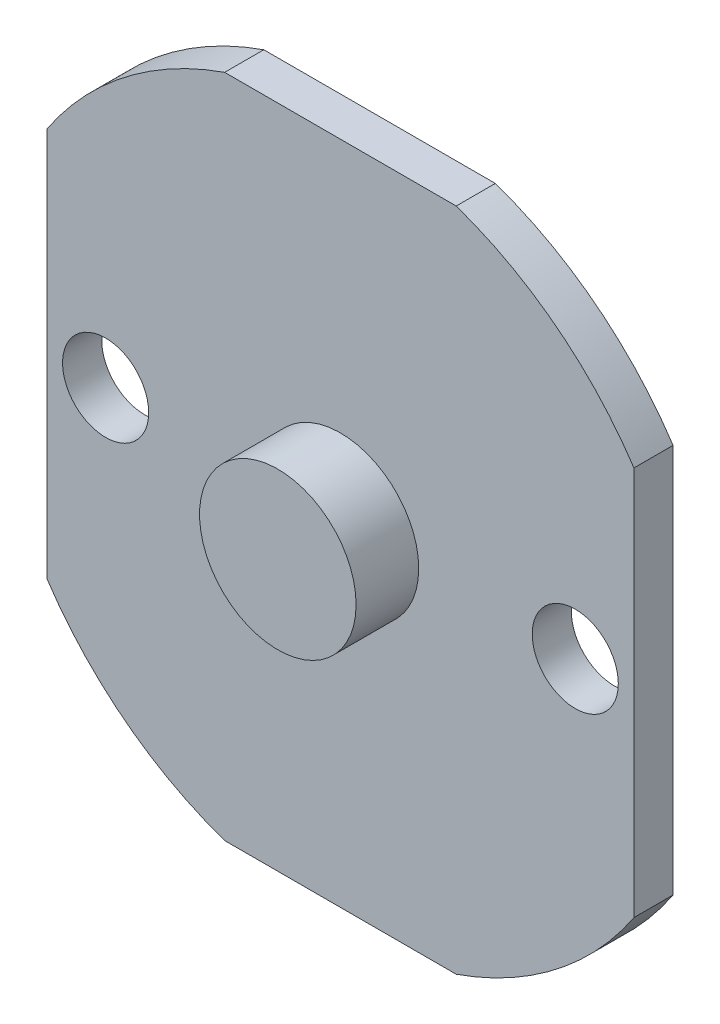
SolidWorks part; units mm, degrees
ref_plane "前视基准面" through (0, 0, 0) normal (0, 0, 1) x (1, 0, 0)
ref_plane "上视基准面" through (0, 0, 0) normal (0, 1, 0) x (1, 0, 0)
ref_plane "右视基准面" through (0, 0, 0) normal (1, 0, 0) x (0, 0, -1)
sketch "草图1" plane through (0, 0, 0) normal (0, 0, 1) x (1, 0, 0)
  circle A0 centre (0, 0) radius 9
  circle A1 centre (0, 0) radius 6 construction
  circle A2 centre (6, 0) radius 1.1
  circle A3 centre (-6, 0) radius 1.1
  dimension "D1" = 18
  dimension "D2" = 12
  dimension "D3" = 2.2
  dimension "D4" = 2
extrude "凸台-拉伸1" add sketch "草图1" along normal blind 1
sketch "草图2" plane through (0, 0, 1) normal (0, 0, 1) x (1, 0, 0)
  line L1 (-7.5, 8.5) -> (7.5, 8.5)
  line L2 (-7.5, 8.5) -> (-7.5, -8.5)
  line L3 (-7.5, -8.5) -> (7.5, -8.5)
  line L4 (7.5, 8.5) -> (7.5, -8.5)
  line L5 (-7.5, 8.5) -> (7.5, -8.5) construction
  line L6 (-7.5, -8.5) -> (7.5, 8.5) construction
  line L7 (-16.1947, 13.0603) -> (16.1947, 13.0603)
  line L8 (-16.1947, 13.0603) -> (-16.1947, -13.0603)
  line L9 (-16.1947, -13.0603) -> (16.1947, -13.0603)
  line L10 (16.1947, 13.0603) -> (16.1947, -13.0603)
  line L11 (-16.1947, 13.0603) -> (16.1947, -13.0603) construction
  line L12 (-16.1947, -13.0603) -> (16.1947, 13.0603) construction
  point P0 (0, 0)
  point P6 (0, 0)
  dimension "D1" = 17
  dimension "D2" = 15
extrude "切除-拉伸1" cut sketch "草图2" against normal blind 2
sketch "草图3" plane through (0, 0, 1) normal (0, 0, 1) x (1, 0, 0)
  circle A0 centre (0, 0) radius 2
extrude "凸台-拉伸2" add sketch "草图3" along normal blind 1.6
